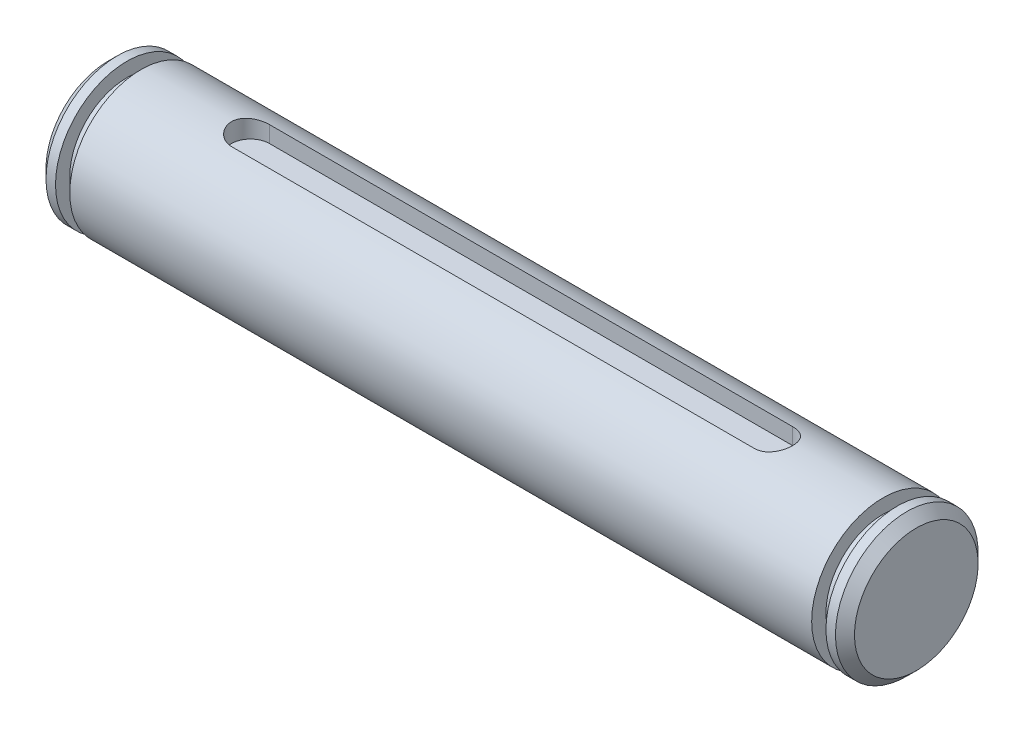
SolidWorks part; units mm, degrees
material "Plain Carbon Steel"
ref_plane "Front Plane" through (0, 0, 0) normal (0, 0, 1) x (1, 0, 0)
ref_plane "Top Plane" through (0, 0, 0) normal (0, 1, 0) x (1, 0, 0)
ref_plane "Right Plane" through (0, 0, 0) normal (1, 0, 0) x (0, 0, -1)
sketch "Sketch1" plane through (0, 0, 0) normal (0, 0, 1) x (1, 0, 0)
  line L0 (-42.5, 0) -> (-42.5, 7.5)
  line L1 (-42.5, 0) -> (42.5, 0)
  line L2 (-42.5, 7.5) -> (-40.5, 7.5)
  line L3 (-40.5, 7.5) -> (-40.5, 6)
  line L4 (-40.5, 6) -> (-39, 6)
  line L5 (-39, 6) -> (-39, 7.5)
  line L6 (-39, 7.5) -> (39, 7.5)
  line L7 (-47.152, 0) -> (-42.5, 0) construction
  line L8 (0, 7.5) -> (0, 0) construction
  line L9 (39, 6) -> (39, 7.5)
  line L10 (40.5, 6) -> (39, 6)
  line L11 (40.5, 7.5) -> (40.5, 6)
  line L12 (42.5, 7.5) -> (40.5, 7.5)
  line L13 (42.5, 0) -> (42.5, 7.5)
  dimension "D1" = 15
  dimension "D2" = 78
  dimension "D3" = 1.5
  dimension "D4" = 12
  dimension "D5" = 2
revolve "Revolve1" add sketch "Sketch1" angle 360 about L7
chamfer "Chamfer1" distance 1 angle 45 2 edges at (42.5, 0, 7.5) (-42.5, 0, 7.5)
sketch "Sketch3" plane through (0, 0, 0) normal (1, 0, 0) x (0, 0, -1)
  line L0 (2, 9.5) -> (2, 5.5)
  line L1 (2, 9.5) -> (-2, 9.5)
  line L2 (2, 5.5) -> (-2, 5.5)
  line L3 (-2, 9.5) -> (-2, 5.5)
  line L4 (2, 9.5) -> (-2, 5.5) construction
  line L5 (2, 5.5) -> (-2, 9.5) construction
  line L6 (0, 7.5) -> (0, 0) construction
  circle A0 centre (0, 0) radius 7.5 construction
  point P1 (0, 7.5)
  dimension "D1" = 4
  dimension "D2" = 4
extrude "Cut-Extrude1" cut sketch "Sketch3" against normal blind 10
sketch "Sketch4" plane through (0, 5.5, 0) normal (0, 1, 0) x (1, 0, 0)
  line L0 (27.5, 0) -> (-27.5, 0) construction
  line L1 (0, -2) -> (0, 2) construction
  line L2 (27.5, -2) -> (-27.5, -2)
  line L3 (27.5, 2) -> (-27.5, 2)
  line L4 (-10, 2) -> (0, 2) construction
  arc A0 (27.5, -2) -> (27.5, 2) centre (27.5, 0) ccw
  arc A1 (-27.5, 2) -> (-27.5, -2) centre (-27.5, 0) ccw
  point P4 (0, 0)
  dimension "D1" = 55
extrude "Cut-Extrude2" cut sketch "Sketch4" along normal blind 10
